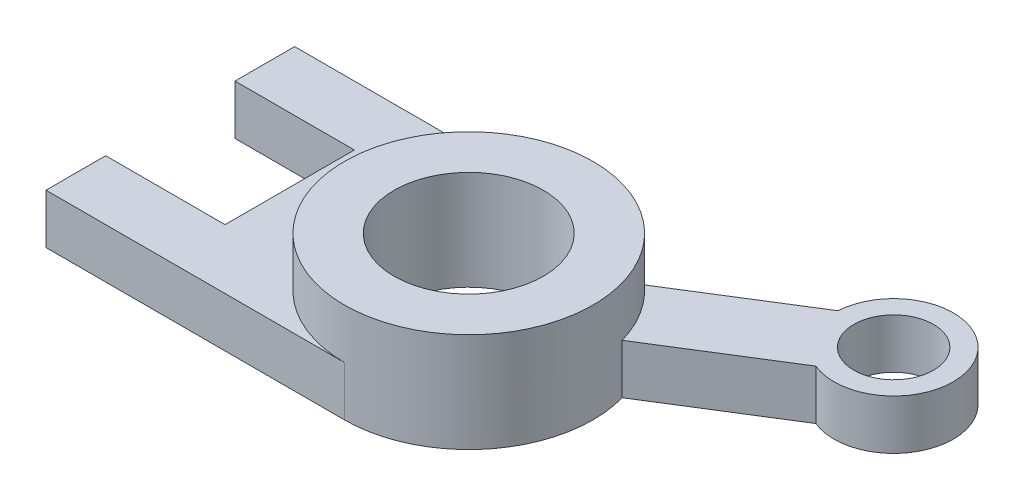
SolidWorks part; units mm, degrees
ref_plane "前视基准面" through (0, 0, 0) normal (0, 0, 1) x (1, 0, 0)
ref_plane "上视基准面" through (0, 0, 0) normal (0, 1, 0) x (1, 0, 0)
ref_plane "右视基准面" through (0, 0, 0) normal (1, 0, 0) x (0, 0, -1)
sketch "草图2" plane through (0, 0, 0) normal (0, 1, 0) x (1, 0, 0)
  line L0 (-104.0812, 0) -> (102.6766, 0) construction
  line L2 (0, 70.0898) -> (0, -90.3161) construction
sketch "草图3" plane through (0, 0, 0) normal (0, 1, 0) x (1, 0, 0)
  line L0 (0, 200070.0898) -> (0, -200090.3161) construction
  line L1 (0, -12.5) -> (-30, -12.5)
  line L3 (0, 12.5) -> (-30, 12.5)
  line L4 (-30, -12.5) -> (-30, -6.5)
  line L5 (-200104.0812, 0) -> (200102.6766, 0) construction
  line L6 (-30, 6.5) -> (-30, 12.5)
  line L7 (-30, 6.5) -> (-18, 6.5)
  line L9 (-30, -6.5) -> (-18, -6.5)
  line L10 (-18, 6.5) -> (-18, -6.5)
  line L12 (12.0313, 3.3909) -> (24.0113, 10.8768)
  line L13 (8.3219, 9.3272) -> (20.3019, 16.8132)
  arc A0 (0, -12.5) -> (12.0313, 3.3909) centre (0, 0) ccw
  arc A3 (24.0113, 10.8768) -> (20.3019, 16.8132) centre (26.2895, 16.4275) ccw
  arc A4 (8.3219, 9.3272) -> (0, 12.5) centre (0, 0) ccw
  dimension "D1" = 6.5
  dimension "D2" = 6.5
sketch "草图4" plane through (0, 0, 0) normal (0, 1, 0) x (1, 0, 0)
  line L1 (12.0313, 3.3909) -> (24.0113, 10.8768)
  line L2 (8.3219, 9.3272) -> (20.3019, 16.8132)
  circle A0 centre (0, 0) radius 12.5
  circle A1 centre (0, 0) radius 7.5
  circle A2 centre (26.2895, 16.4275) radius 4
  circle A3 centre (26.2895, 16.4275) radius 6
  point P0 (0, 0)
  point P5 (0, 12.5)
  point P6 (0, -12.5)
  point P7 (0, 12.5)
  point P11 (10.6006, 6.624)
  point P13 (21.2012, 13.248)
  point P18 (0, 0)
  point P19 (0, 0)
extrude "凸台-拉伸2" add sketch "草图3" along normal blind 5
extrude "切除-拉伸1" cut sketch "草图4" along normal blind 5 contours A2
ref_plane "基准面1" through (0, 5, 0) normal (0, 1, 0) x (1, 0, 0)
sketch "草图6" plane through (0, 5, 0) normal (0, 1, 0) x (1, 0, 0)
  circle A0 centre (0, 0) radius 12.5
extrude "凸台-拉伸3" add sketch "草图6" along normal blind 5
sketch "草图8" plane through (0, 5, 0) normal (0, 1, 0) x (1, 0, 0)
  circle A0 centre (0, 0) radius 7.5
extrude "切除-拉伸2" cut sketch "草图8" against normal mid plane 10
